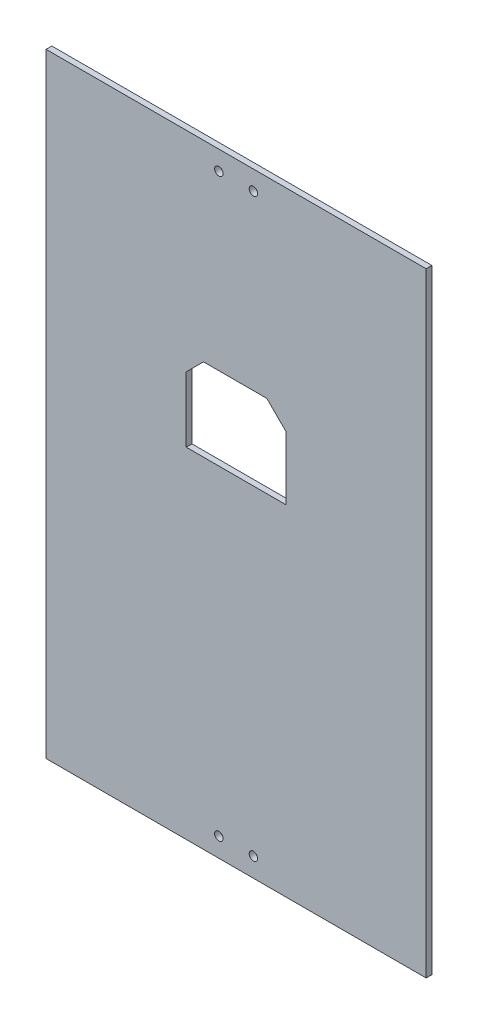
SolidWorks part; units mm, degrees
ref_plane "Plan de face" through (0, 0, 0) normal (0, 0, 1) x (1, 0, 0)
ref_plane "Plan de dessus" through (0, 0, 0) normal (0, 1, 0) x (1, 0, 0)
ref_plane "Plan de droite" through (0, 0, 0) normal (1, 0, 0) x (0, 0, -1)
sketch "Esquisse1" plane through (0, 0, 0) normal (0, 0, 1) x (1, 0, 0)
  line L0 (0, 0) -> (99, 0) construction
  line L1 (0, 0) -> (-99, 0) construction
  line L2 (-99, 0) -> (-99, 165) construction
  line L3 (-99, 165) -> (99, 165)
  line L4 (99, 165) -> (99, -155)
  line L5 (99, -155) -> (-99, -155)
  line L7 (-99, 165) -> (-99, -155)
  dimension "D1" = 165
  dimension "D2" = 99
  dimension "D4" = 320
  dimension "D5" = 320
extrude "Boss.-Extru.1" add sketch "Esquisse1" along normal blind 3
sketch "Esquisse2" plane through (0, 0, 3) normal (0, 0, 1) x (1, 0, 0)
  line L0 (0, -155) -> (0, -145) construction
  line L1 (-99, -155) -> (99, -155) construction
  line L2 (0, -145) -> (9, -145) construction
  line L3 (0, -145) -> (-9, -145) construction
  line L4 (0, 165) -> (0, 155) construction
  line L5 (99, 165) -> (-99, 165) construction
  line L6 (0, 155) -> (9, 155) construction
  line L7 (0, 155) -> (-9, 155) construction
  circle A0 centre (9, -145) radius 2.2
  circle A1 centre (-9, -145) radius 2.2
  circle A2 centre (-9, 155) radius 2.2
  circle A3 centre (9, 155) radius 2.2
  dimension "D1" = 10
  dimension "D4" = 10
  dimension "D2" = 18
  dimension "D3" = 9
  dimension "D5" = 18
  dimension "D6" = 9
extrude "Enlèv. mat.-Extru.1" cut sketch "Esquisse2" against normal up to next
sketch "Esquisse3" plane through (0, 0, 3) normal (0, 0, 1) x (1, 0, 0)
  line L0 (-99, 165) -> (-99, 89)
  line L1 (-99, 165) -> (-99, -155) construction
  line L2 (-99, 89) -> (99, 89)
  line L3 (99, -155) -> (99, 165) construction
  line L4 (99, 89) -> (99, 165)
  line L5 (99, 165) -> (-99, 165)
sketch "Esquisse5" plane through (0, 0, 3) normal (0, 0, 1) x (1, 0, 0)
  line L0 (0, -155) -> (0, 22) construction
  line L1 (-99, -155) -> (99, -155) construction
  line L2 (0, 22) -> (26, 22)
  line L3 (0, 22) -> (-26, 22)
  line L4 (-26, 22) -> (-26, 56)
  line L5 (-26, 56) -> (-26, 65) construction
  line L6 (-26, 65) -> (-17, 65) construction
  line L7 (-17, 65) -> (-26, 56)
  line L8 (26, 22) -> (26, 55)
  line L9 (26, 55) -> (26, 65) construction
  line L10 (26, 65) -> (16, 65) construction
  line L11 (16, 65) -> (-17, 65)
  line L12 (26, 55) -> (16, 65)
  dimension "D1" = 177
  dimension "D2" = 26
  dimension "D3" = 26
  dimension "D4" = 34
  dimension "D5" = 9
  dimension "D6" = 9
extrude "Enlèv. mat.-Extru.3" cut sketch "Esquisse5" against normal up to next
